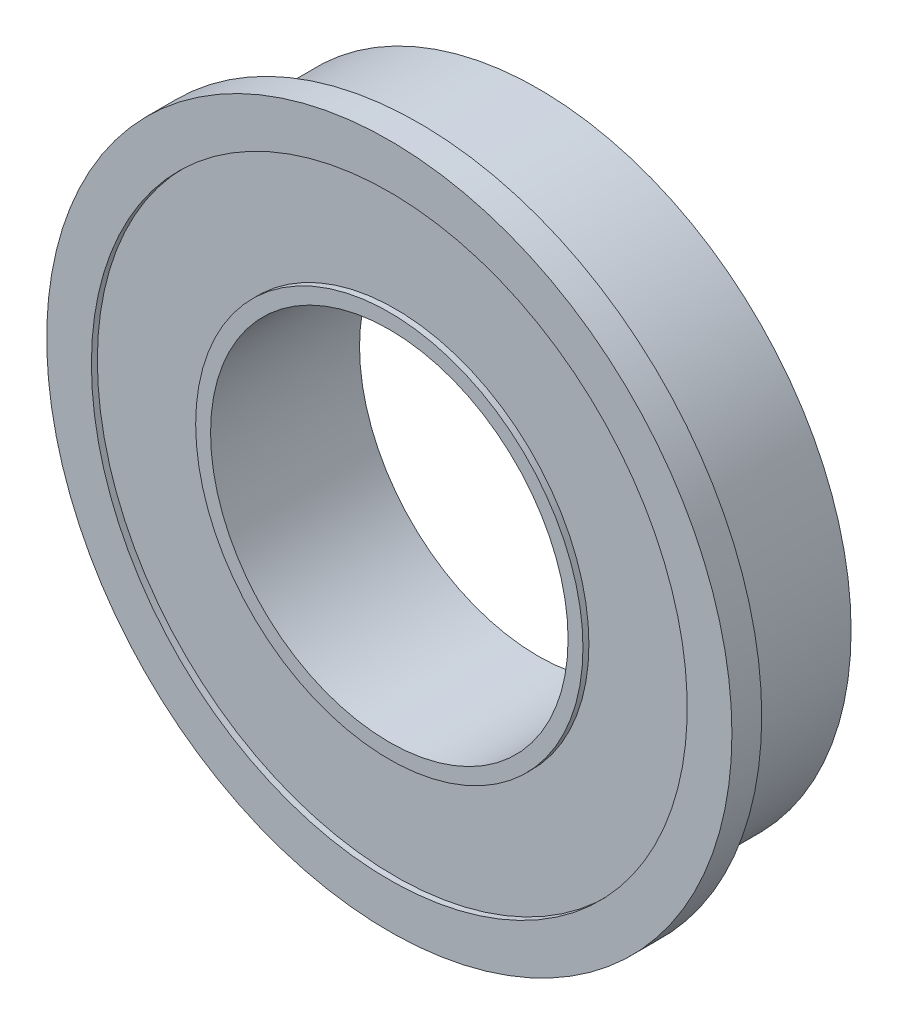
SolidWorks part; units mm, degrees
ref_plane "前视基准面" through (0, 0, 0) normal (0, 0, 1) x (1, 0, 0)
ref_plane "上视基准面" through (0, 0, 0) normal (0, 1, 0) x (1, 0, 0)
ref_plane "右视基准面" through (0, 0, 0) normal (1, 0, 0) x (0, 0, -1)
sketch "草图1" plane through (0, 0, 0) normal (0, 0, 1) x (1, 0, 0)
  circle A0 centre (0, 0) radius 10.5
  circle A1 centre (0, 0) radius 11.5
  dimension "D1" = 21
  dimension "D2" = 23
extrude "凸台-拉伸1" add sketch "草图1" along normal blind 1
sketch "草图2" plane through (0, 0, 1) normal (0, 0, 1) x (1, 0, 0)
  circle A0 centre (0, 0) radius 10.5
  circle A1 centre (0, 0) radius 6
  circle A3 centre (0, 0) radius 10.5 construction
  dimension "D2" = 12
extrude "凸台-拉伸2" add sketch "草图2" against normal blind 5
sketch "草图3" plane through (0, 0, -4) normal (0, 0, -1) x (-1, 0, 0)
  circle A0 centre (0, 0) radius 6.5
  circle A1 centre (0, 0) radius 10
  circle A2 centre (0, 0) radius 10.5 construction
  circle A3 centre (0, 0) radius 6 construction
  dimension "D1" = 0.5
  dimension "D2" = 0.5
extrude "切除-拉伸1" cut sketch "草图3" against normal blind 0.2
ref_plane "基准面1" through (0, 0, -1.5) normal (0, 0, -1) x (-1, 0, 0)
mirror "镜向1" about plane through (0, 0, -1.5) normal (0, 0, -1) of "切除-拉伸1"
